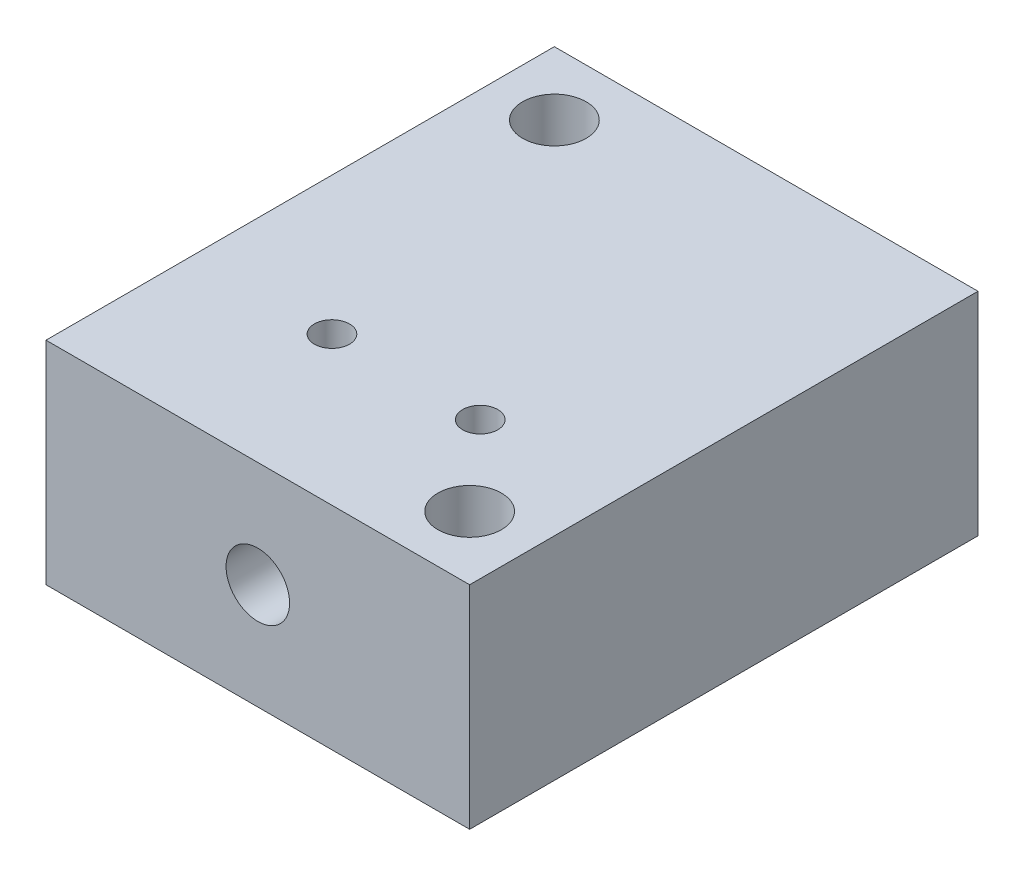
SolidWorks part; units mm, degrees
ref_plane "Ebene vorne" through (0, 0, 0) normal (0, 0, 1) x (1, 0, 0)
ref_plane "Ebene oben" through (0, 0, 0) normal (0, 1, 0) x (1, 0, 0)
ref_plane "Ebene rechts" through (0, 0, 0) normal (1, 0, 0) x (0, 0, -1)
sketch "Skizze1" plane through (0, 0, 0) normal (0, 0, 1) x (1, 0, 0)
  line L1 (50, -25) -> (-50, -25)
  line L2 (50, -25) -> (50, 25)
  line L3 (50, 25) -> (-50, 25)
  line L4 (-50, -25) -> (-50, 25)
  line L5 (50, -25) -> (-50, 25) construction
  line L6 (50, 25) -> (-50, -25) construction
  point P1 (0, 0)
  dimension "D1" = 50
  dimension "D2" = 100
extrude "Aufsatz-Linear austragen1" add sketch "Skizze1" along normal blind 120
sketch "Skizze2" plane through (0, 25, 0) normal (0, 1, 0) x (1, 0, 0)
  line L0 (50, -120) -> (-50, -120) construction
  line L1 (50, -120) -> (50, 0) construction
  line L2 (-50, -120) -> (-50, 0) construction
  line L3 (50, 0) -> (-50, 0) construction
  circle A0 centre (-35, -15) radius 15
  circle A1 centre (35, -105) radius 15
  dimension "D1" = 30
  dimension "D2" = 30
hole_wizard "Stirnsenkung für M8 Senkschraube (Kopf Button)1" positions "Skizze4" profile "Skizze5" counterbore size "M8" standard "ANSI Metrisch" end condition through all
sketch "Skizze4" plane through (0, 25, 0) normal (0, 1, 0) x (1, 0, 0)
  point P0 (35, -105)
  point P5 (-35, -15)
sketch "Skizze5" plane through (35, 25, 105) normal (1, 0, 0) x (0, 0, 1)
  line L0 (0, 0) -> (0, 50)
  line L1 (0, 50) -> (4.5, 50)
  line L3 (4.5, 50) -> (4.5, 45)
  line L4 (4.5, 45) -> (7.5, 45)
  line L5 (7.5, 45) -> (7.5, 0)
  line L7 (7.5, 0) -> (0, 0)
  line L11 (0, -6.35) -> (0, 107.95) construction
  dimension "Bohrerdurchmesser" = 9
  dimension "Bohrungstiefe" = 50
  dimension "Senkdurchmesser2" = 15
  dimension "Senktiefe2" = 45
sketch "Skizze6" plane through (0, 0, 120) normal (0, 0, 1) x (1, 0, 0)
  line L0 (-50, 25) -> (50, -25)
  line L1 (50, 25) -> (-50, -25)
hole_wizard "Stirnsenkung für M8 Senkschraube (Kopf Button)2" positions "Skizze8" profile "Skizze7" counterbore size "M8" standard "ANSI Metrisch" end condition through all
sketch "Skizze8" plane through (0, 0, 120) normal (0, 0, 1) x (1, 0, 0)
  point P0 (0, 0)
sketch "Skizze7" plane through (0, 0, 120) normal (1, 0, 0) x (0, -1, 0)
  line L0 (0, 0) -> (0, 120)
  line L1 (0, 120) -> (4.5, 120)
  line L3 (4.5, 120) -> (4.5, 116)
  line L4 (4.5, 116) -> (7.5, 116)
  line L5 (7.5, 116) -> (7.5, 0)
  line L7 (7.5, 0) -> (0, 0)
  line L11 (0, -6.35) -> (0, 107.95) construction
  dimension "Bohrerdurchmesser" = 9
  dimension "Bohrungstiefe" = 120
  dimension "Senkdurchmesser2" = 15
  dimension "Senktiefe2" = 116
hole_wizard "Kernloch für M8 Helicoil1" positions "Skizze10" profile "Skizze9" hole size "M8x1.25" standard "ANSI Metrisch"
sketch "Skizze10" plane through (0, 25, 0) normal (0, 1, 0) x (1, 0, 0)
  point P0 (-17.5, -85)
  point P3 (17.5, -85)
sketch "Skizze9" plane through (-17.5, 25, 85) normal (1, 0, 0) x (0, 0, 1)
  line L0 (0, 0) -> (0, 22.4936)
  line L1 (0, 22.4936) -> (4.15, 20)
  line L2 (4.15, 20) -> (4.15, 0)
  line L5 (4.15, 0) -> (0, 0)
  line L10 (0, 22.4936) -> (-4.15, 20) construction
  line L11 (0, -6.35) -> (0, 107.95) construction
  dimension "Bohrerdurchmesser" = 8.3
  dimension "Bohrungstiefe" = 20
  dimension "Spitzenwinkel" = 118
